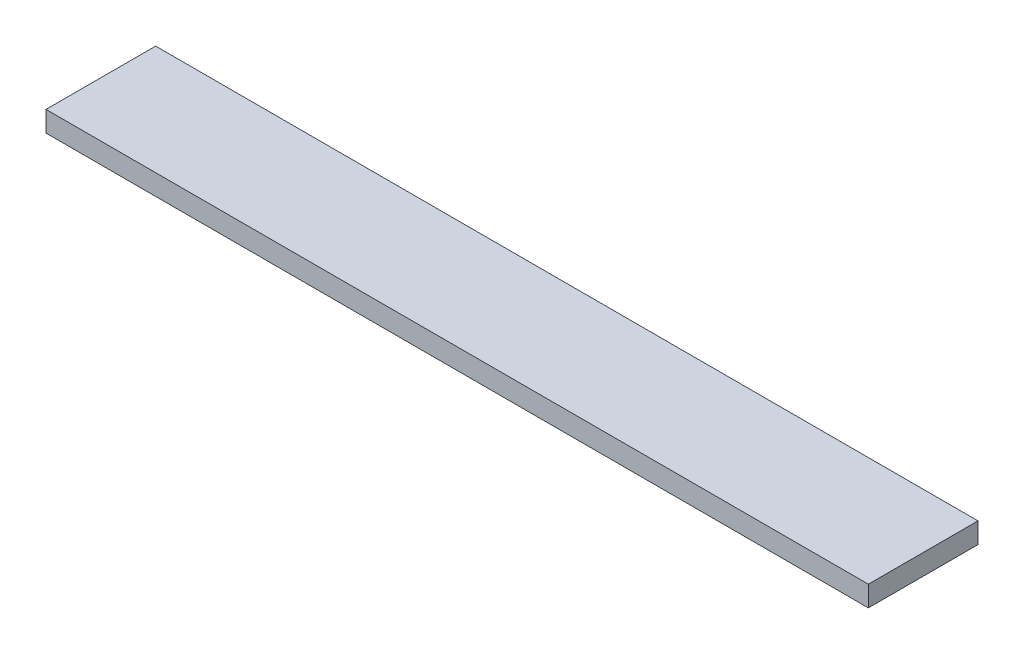
SolidWorks part; units mm, degrees
material "Pino"
ref_plane "Alzado" through (0, 0, 0) normal (0, 0, 1) x (1, 0, 0)
ref_plane "Planta" through (0, 0, 0) normal (0, 1, 0) x (1, 0, 0)
ref_plane "Vista lateral" through (0, 0, 0) normal (1, 0, 0) x (0, 0, -1)
sketch "Croquis1" plane through (0, 0, 0) normal (0, 1, 0) x (1, 0, 0)
  line L1 (-762, -101.6) -> (762, -101.6)
  line L2 (-762, -101.6) -> (-762, 101.6)
  line L3 (-762, 101.6) -> (762, 101.6)
  line L4 (762, -101.6) -> (762, 101.6)
  line L5 (-762, -101.6) -> (762, 101.6) construction
  line L6 (-762, 101.6) -> (762, -101.6) construction
  point P0 (0, 0)
  dimension "D1" = 203.2
  dimension "D2" = 1524
extrude "Saliente-Extruir1" add sketch "Croquis1" along normal blind 38.1
